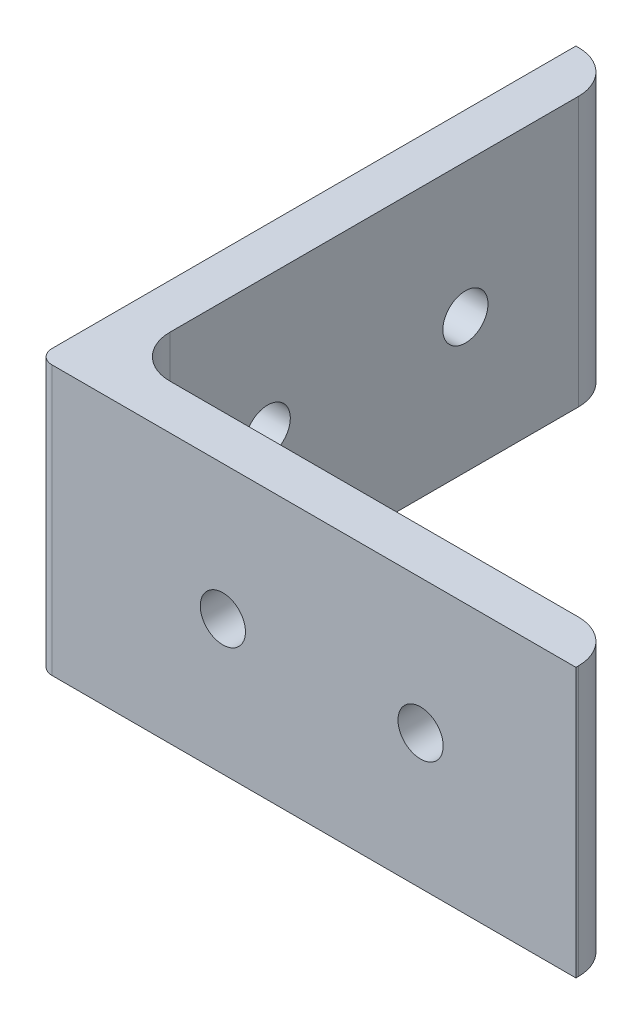
SolidWorks part; units mm, degrees
ref_plane "Front Plane" through (0, 0, 0) normal (0, 0, 1) x (1, 0, 0)
ref_plane "Top Plane" through (0, 0, 0) normal (0, 1, 0) x (1, 0, 0)
ref_plane "Right Plane" through (0, 0, 0) normal (1, 0, 0) x (0, 0, -1)
sketch "Sketch1" plane through (0, 0, 0) normal (0, 1, 0) x (1, 0, 0)
  line L0 (0, 0) -> (0, 38.1)
  line L1 (0, 38.1) -> (3.175, 38.1)
  line L2 (3.175, 38.1) -> (3.175, 3.175)
  line L3 (3.175, 3.175) -> (38.1, 3.175)
  line L4 (38.1, 3.175) -> (38.1, 0)
  line L5 (38.1, 0) -> (0, 0)
  dimension "D1" = 38.1
  dimension "D2" = 3.175
extrude "Boss-Extrude1" add sketch "Sketch1" along normal blind 19.05
fillet "Fillet1" radius 3 3 edges at (38.1, 9.525, -3.175) (3.175, 9.525, -3.175) (3.175, 9.525, -38.1)
fillet "Fillet2" radius 1 1 edges at (0, 9.525, 0)
sketch "Sketch2" plane through (0, 0, 0) normal (0, 0, 1) x (1, 0, 0)
  line L0 (13.1, 9.525) -> (27.1, 9.525) construction
  line L1 (27.1, 9.525) -> (38.1, 9.525) construction
  line L2 (38.1, 19.05) -> (38.1, 0) construction
  circle A0 centre (13.1, 9.525) radius 1.6
  circle A1 centre (27.1, 9.525) radius 1.6
  dimension "D1" = 14
  dimension "D3" = 3.2
  dimension "D2" = 11
extrude "Cut-Extrude1" cut sketch "Sketch2" against normal through all
sketch "Sketch3" plane through (0, 0, 0) normal (-1, 0, 0) x (0, 0, 1)
  line L0 (-38.1, 9.525) -> (-27.1, 9.525) construction
  line L1 (-38.1, 19.05) -> (-38.1, 0) construction
  line L2 (-27.1, 9.525) -> (-13.1, 9.525) construction
  circle A0 centre (-27.1, 9.525) radius 1.6
  circle A1 centre (-13.1, 9.525) radius 1.6
  dimension "D1" = 3.2
  dimension "D2" = 14
  dimension "D3" = 11
extrude "Cut-Extrude2" cut sketch "Sketch3" against normal through all
